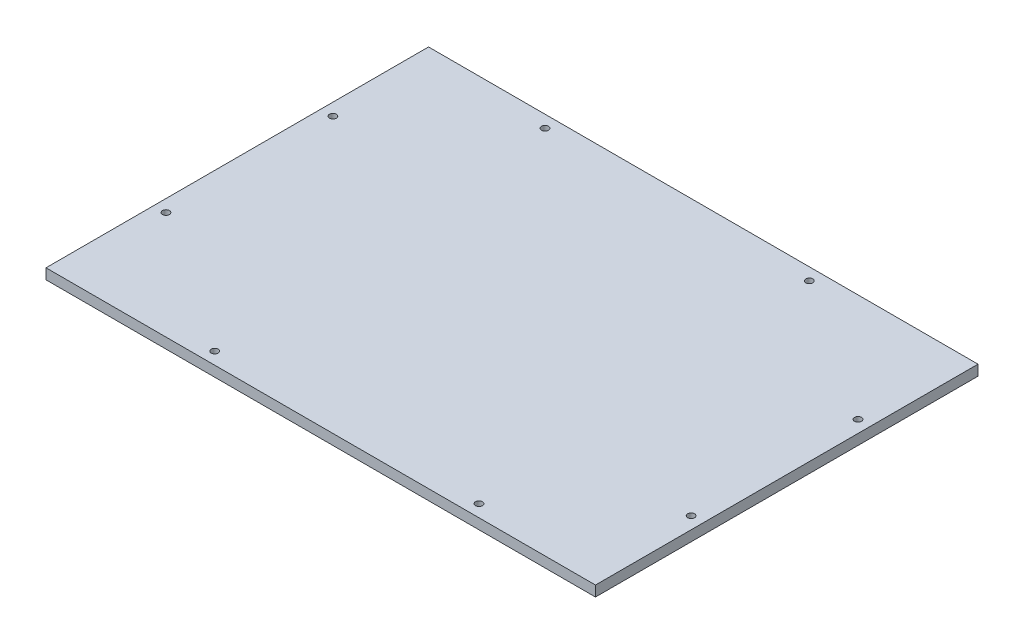
SolidWorks part; units mm, degrees
material "PC High Viscosity"
ref_plane "Front Plane" through (0, 0, 0) normal (0, 0, 1) x (1, 0, 0)
ref_plane "Top Plane" through (0, 0, 0) normal (0, 1, 0) x (1, 0, 0)
ref_plane "Right Plane" through (0, 0, 0) normal (1, 0, 0) x (0, 0, -1)
sketch "Sketch1" plane through (0, 0, 0) normal (0, 1, 0) x (1, 0, 0)
  line L1 (8.4883, 0) -> (510.1383, 0)
  line L2 (8.4883, 0) -> (8.4883, -349.25)
  line L3 (8.4883, -349.25) -> (510.1383, -349.25)
  line L4 (510.1383, 0) -> (510.1383, -349.25)
  dimension "D1" = 501.65
  dimension "D2" = 349.25
extrude "Boss-Extrude1" add sketch "Sketch1" along normal blind 9.525
sketch "Sketch2" plane through (0, 9.525, 0) normal (0, 1, 0) x (1, 0, 0)
  circle A0 centre (392.6633, -338.1375) radius 3.175
  circle A1 centre (151.3633, -338.1375) radius 3.175
  circle A2 centre (367.2633, -11.1125) radius 3.175
  circle A3 centre (125.9633, -11.1125) radius 3.175
  circle A4 centre (19.6008, -250.825) radius 3.175
  circle A5 centre (19.6008, -98.425) radius 3.175
  circle A6 centre (499.0258, -250.825) radius 3.175
  circle A7 centre (499.0258, -98.425) radius 3.175
extrude "Cut-Extrude1" cut sketch "Sketch2" against normal up to surface (9.525 mm away) up to face at (259.3133, 0, 174.625)
sketch "Sketch3" plane through (0, 9.525, 0) normal (0, 1, 0) x (1, 0, 0)
  line L0 (472.0383, -349.25) -> (472.0383, 3.175) construction
  line L1 (510.1383, -349.25) -> (8.4883, -349.25) construction
  line L2 (513.3133, 3.175) -> (5.3133, 3.175) construction
  line L3 (510.1383, 0) -> (510.1383, -349.25) construction
  line L4 (46.5883, -349.25) -> (46.5883, 0) construction
  line L5 (8.4883, 0) -> (510.1383, 0) construction
  line L6 (8.4883, -349.25) -> (8.4883, 0) construction
  line L7 (510.1383, -311.15) -> (8.4883, -311.15) construction
  line L8 (510.1383, -38.1) -> (8.4883, -38.1) construction
  point P18 (472.0383, -311.15)
  point P19 (472.0383, -38.1)
  point P20 (46.5883, -38.1)
  point P21 (46.5883, -311.15)
  dimension "D1" = 38.1
  dimension "D2" = 38.1
  dimension "D3" = 38.1
  dimension "D4" = 38.1
